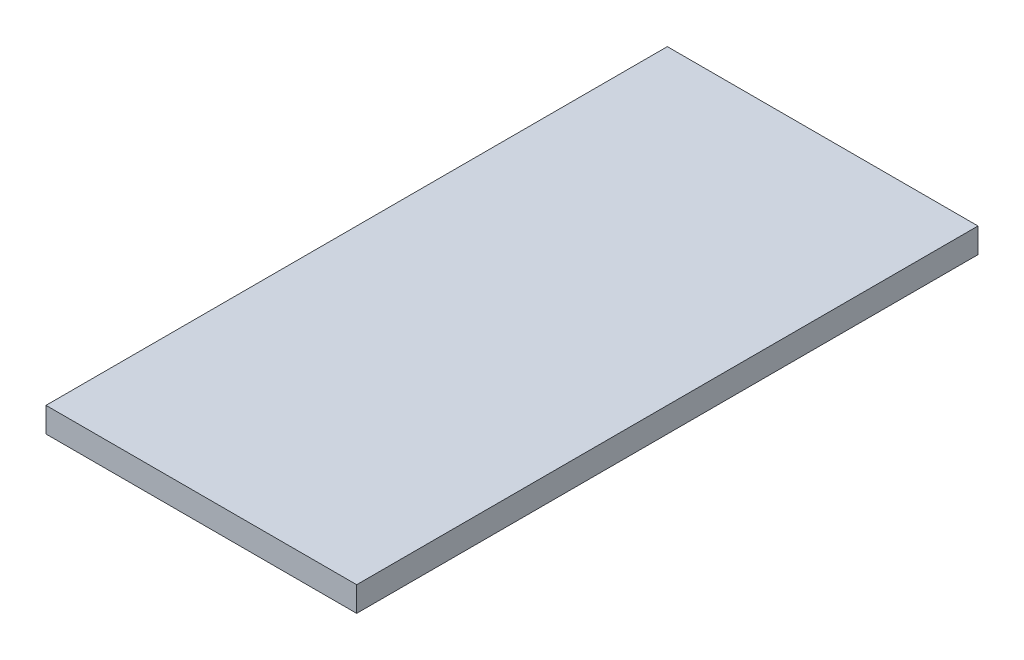
SolidWorks part; units mm, degrees
ref_plane "Front Plane" through (0, 0, 0) normal (0, 0, 1) x (1, 0, 0)
ref_plane "Top Plane" through (0, 0, 0) normal (0, 1, 0) x (1, 0, 0)
ref_plane "Right Plane" through (0, 0, 0) normal (1, 0, 0) x (0, 0, -1)
sketch "Sketch1" plane through (0, 0, 0) normal (0, 1, 0) x (1, 0, 0)
  line L1 (-100, -200) -> (100, -200)
  line L2 (-100, -200) -> (-100, 200)
  line L3 (-100, 200) -> (100, 200)
  line L4 (100, -200) -> (100, 200)
  line L5 (-100, -200) -> (100, 200) construction
  line L6 (-100, 200) -> (100, -200) construction
  point P0 (0, 0)
  dimension "D1" = 400
  dimension "D2" = 200
extrude "Boss-Extrude1" add sketch "Sketch1" along normal blind 16 contours L2 L3 L4 L1
